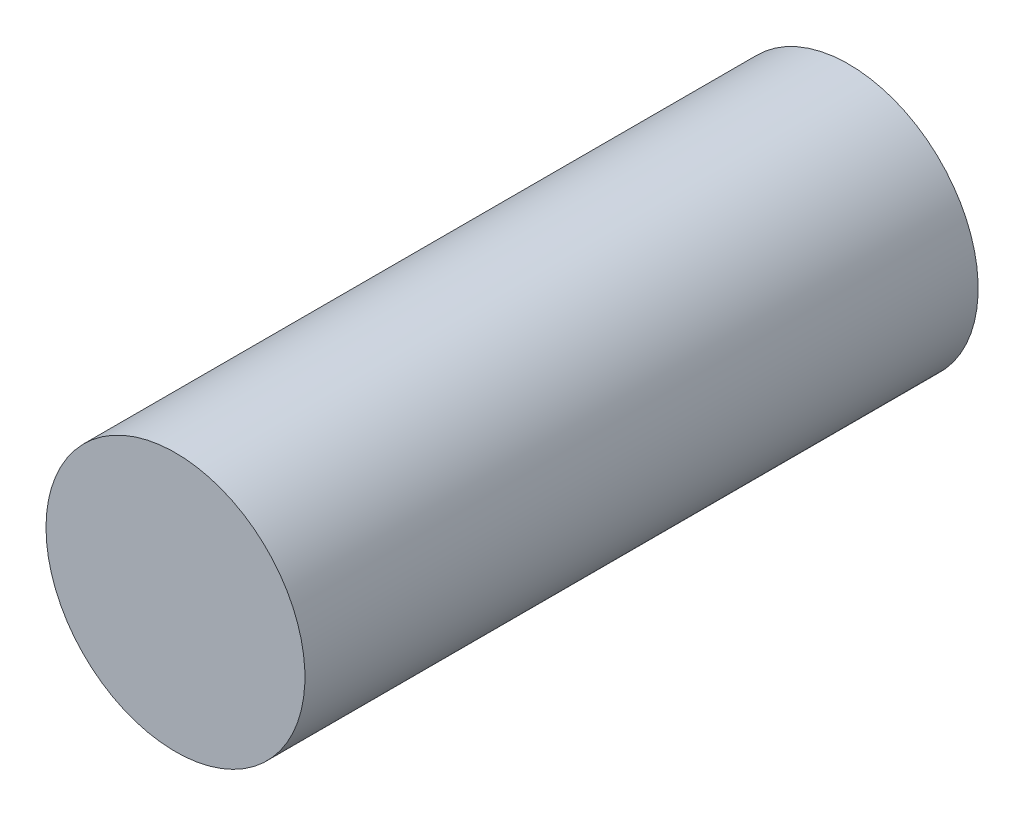
SolidWorks part; units mm, degrees
material "6061-T6 (SS)"
ref_plane "Front Plane" through (0, 0, 0) normal (0, 0, 1) x (1, 0, 0)
ref_plane "Top Plane" through (0, 0, 0) normal (0, 1, 0) x (1, 0, 0)
ref_plane "Right Plane" through (0, 0, 0) normal (1, 0, 0) x (0, 0, -1)
sketch "Body sketch" plane through (0, 0, 0) normal (0, 0, 1) x (1, 0, 0)
  circle A0 centre (0, 0) radius 2.5
extrude "Body" add sketch "Body sketch" along normal blind 13
